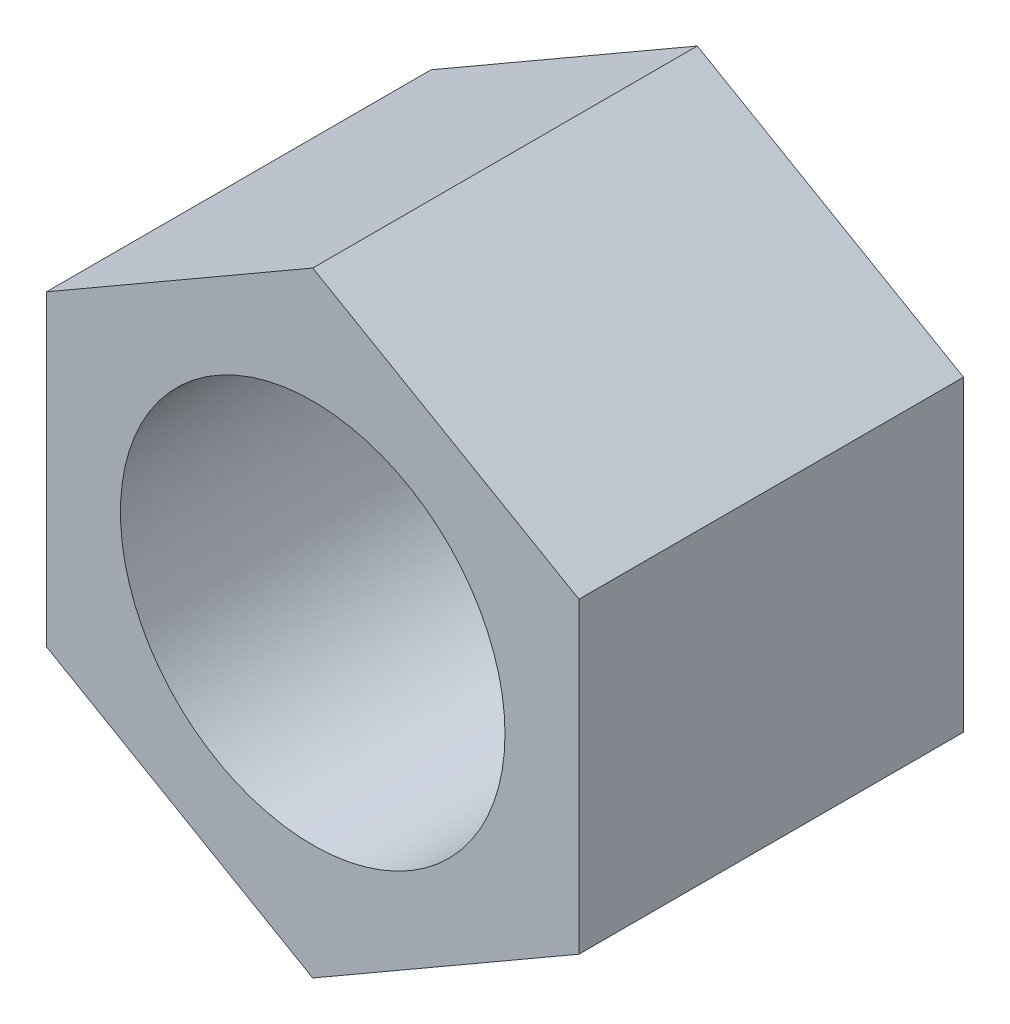
SolidWorks part; units mm, degrees
ref_plane "Front Plane" through (0, 0, 0) normal (0, 0, 1) x (1, 0, 0)
ref_plane "Top Plane" through (0, 0, 0) normal (0, 1, 0) x (1, 0, 0)
ref_plane "Right Plane" through (0, 0, 0) normal (1, 0, 0) x (0, 0, -1)
sketch "Sketch1" plane through (0, 0, 0) normal (0, 0, 1) x (1, 0, 0)
  line L1 (-72.6679, 82.7387) -> (-70.591, 83.9378)
  line L2 (-70.591, 83.9378) -> (-70.591, 86.336)
  line L3 (-70.591, 86.336) -> (-72.6679, 87.5351)
  line L4 (-72.6679, 87.5351) -> (-74.7449, 86.336)
  line L5 (-74.7449, 86.336) -> (-74.7449, 83.9378)
  line L6 (-74.7449, 83.9378) -> (-72.6679, 82.7387)
  circle A0 centre (-72.6679, 85.1369) radius 1.5 construction
  circle A1 centre (-72.6679, 85.1369) radius 1.5
  circle A3 centre (-72.6679, 85.1369) radius 2.0769 construction
extrude "Boss-Extrude1" add sketch "Sketch1" along normal blind 3
